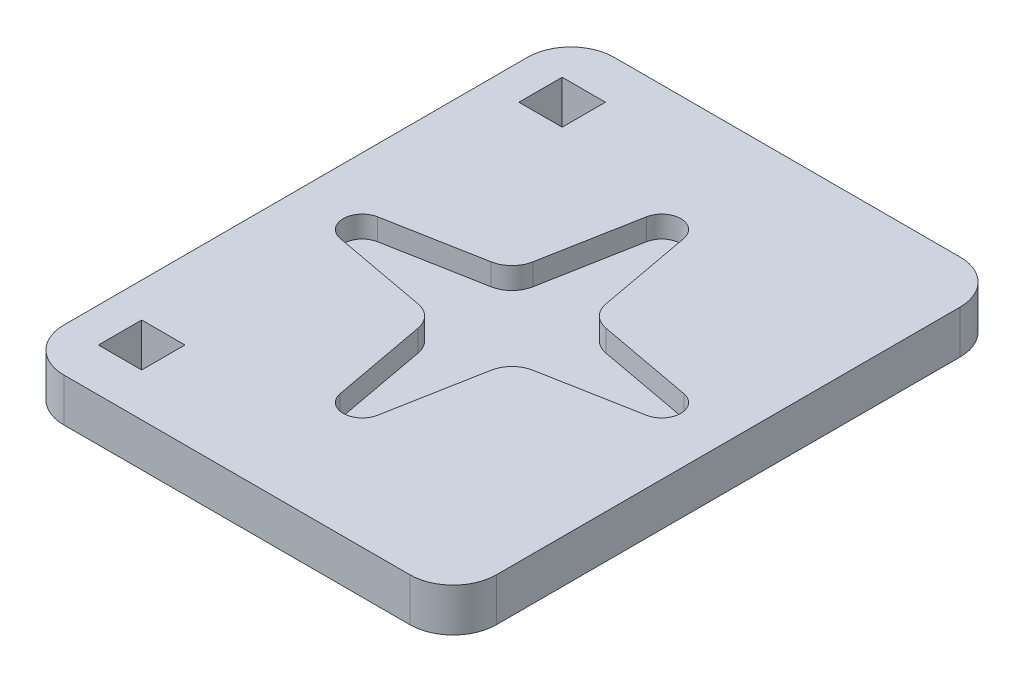
SolidWorks part; units mm, degrees
ref_plane "Front Plane" through (0, 0, 0) normal (0, 0, 1) x (1, 0, 0)
ref_plane "Top Plane" through (0, 0, 0) normal (0, 1, 0) x (1, 0, 0)
ref_plane "Right Plane" through (0, 0, 0) normal (1, 0, 0) x (0, 0, -1)
sketch "Sketch2" plane through (0, 0, 0) normal (0, 1, 0) x (1, 0, 0)
  line L0 (25, 0) -> (25, -63.6) construction
  line L1 (5, 0) -> (45, 0)
  line L2 (0, -5) -> (0, -58.6)
  line L3 (5, -63.6) -> (45, -63.6)
  line L4 (50, -5) -> (50, -58.6)
  line L5 (0, -31.8) -> (50, -31.8) construction
  line L6 (9, -53.6) -> (9, -58.6)
  line L7 (4, -10) -> (9, -10)
  line L8 (4, -10) -> (4, -5)
  line L9 (4, -5) -> (9, -5)
  line L10 (9, -10) -> (9, -5)
  line L11 (4, -10) -> (9, -5) construction
  line L12 (4, -5) -> (9, -10) construction
  line L13 (4, -53.6) -> (9, -53.6)
  line L14 (4, -53.6) -> (4, -58.6)
  line L15 (4, -58.6) -> (9, -58.6)
  line L16 (9, -58.6) -> (4, -53.6) construction
  arc A0 (0, -58.6) -> (5, -63.6) centre (5, -58.6) ccw
  arc A1 (45, -63.6) -> (50, -58.6) centre (45, -58.6) ccw
  arc A2 (50, -5) -> (45, 0) centre (45, -5) ccw
  arc A3 (0, -5) -> (5, 0) centre (5, -5) cw
  point P7 (0, -63.6)
  point P10 (50, -63.6)
  point P13 (50, 0)
  point P16 (0, 0)
  point P21 (6.5, -7.5)
  point P22 (43.5, -25)
  point P31 (6.5, -56.1)
  dimension "D3" = 5
  dimension "D4" = 7.5
  dimension "D5" = 5
  dimension "D1" = 50
  dimension "D2" = 48.6
  dimension "D7" = 5
extrude "Boss-Extrude1" add sketch "Sketch2" along normal blind 5
sketch "Sketch4" plane through (0, 5, 0) normal (0, 1, 0) x (1, 0, 0)
  line L0 (25, -31.8) -> (25, -10.9854) construction
  line L9 (25, 0) -> (25, -50) construction
  line L10 (45, 0) -> (5, 0) construction
  line L12 (0, -31.8) -> (50, -31.8) construction
  line L13 (0, -5) -> (0, -58.6) construction
  line L14 (50, -58.6) -> (50, -5) construction
  point P0 (25, -31.8)
  point P3 (27.6452, -27.2144)
  point P4 (0, 0)
  point P5 (0, 0)
  point P6 (25, -25.3)
  point P7 (24.998, -24.9977)
  point P8 (31.2859, -28.0639)
  point P9 (0, 0)
  point P10 (0, 0)
  point P11 (0, 0)
  point P12 (0, 0)
  point P13 (7.7, -29.6)
  point P15 (25, -31.8)
  point P16 (0, 0)
  point P17 (0, 0)
  point P18 (0, 0)
  point P70 (24.998, -24.9977)
  point P88 (25, -25)
  line B0 (7.2984, -29.637) -> (18.378, -27.5799)
  line B1 (20.7799, -25.178) -> (22.837, -14.0984)
  line B2 (27.163, -14.0984) -> (29.2201, -25.178)
  line B3 (31.622, -27.5799) -> (42.7016, -29.637)
  line B4 (42.7016, -33.963) -> (31.622, -36.0201)
  line B5 (29.2201, -38.422) -> (27.163, -49.5016)
  line B6 (22.837, -49.5016) -> (20.7799, -38.422)
  line B7 (18.378, -36.0201) -> (7.2984, -33.963)
  arc B8 (7.2984, -29.637) -> (5.5, -31.8) centre (7.7, -31.8) ccw
  arc B9 (27.163, -14.0984) -> (22.837, -14.0984) centre (25, -14.5) ccw
  arc B10 (18.378, -27.5799) -> (20.7799, -25.178) centre (17.8303, -24.6303) ccw
  arc B11 (29.2201, -25.178) -> (31.622, -27.5799) centre (32.1697, -24.6303) ccw
  arc B12 (42.7016, -33.963) -> (42.7016, -29.637) centre (42.3, -31.8) ccw
  arc B13 (31.622, -36.0201) -> (29.2201, -38.422) centre (32.1697, -38.9697) ccw
  arc B14 (22.837, -49.5016) -> (27.163, -49.5016) centre (25, -49.1) ccw
  arc B15 (20.7799, -38.422) -> (18.378, -36.0201) centre (17.8303, -38.9697) ccw
  arc B16 (7.2984, -29.637) -> (7.2984, -33.963) centre (7.7, -31.8) ccw
  dimension "D1" = 19.5
  dimension "D2" = 19.5
  dimension "D5" = 6.5
sketch_block_instance "Block1-1"
sketch_block "Block1" parameters "D1"=4.4, "D2"=4.4, "D3"=3
extrude "Cut-Extrude1" cut sketch "Sketch4" against normal blind 2.5 contours B8 B16 B7 B15 B6 B14 B5 B13 B4 B12 B3 B11 B2 B9 B1 B10 B0
